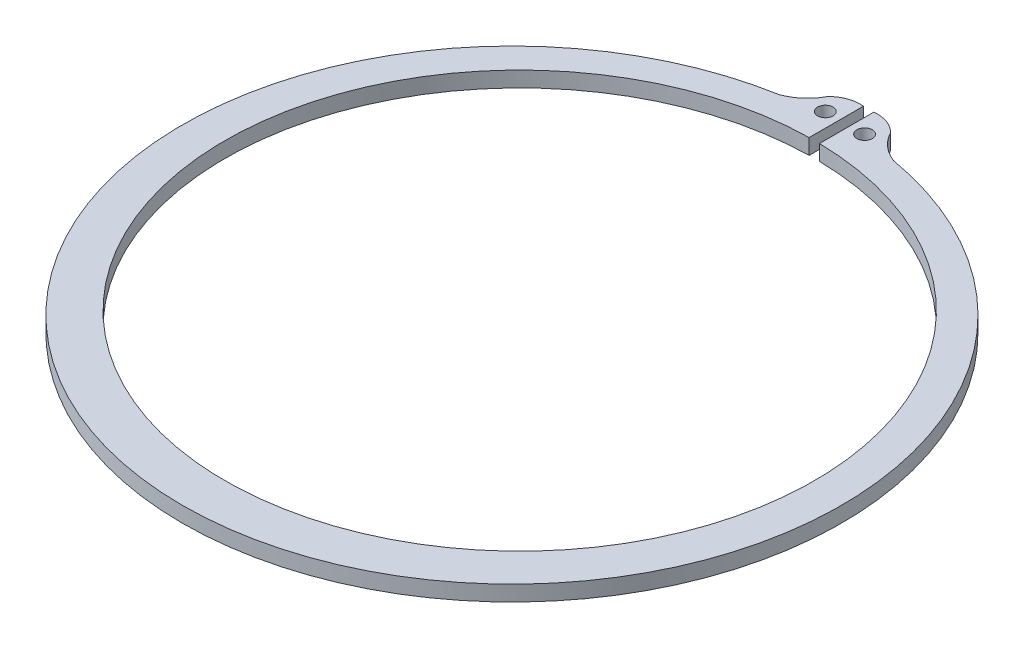
SolidWorks part; units mm, degrees
ref_plane "Plano frontal" through (0, 0, 0) normal (0, 0, 1) x (1, 0, 0)
ref_plane "Plano superior" through (0, 0, 0) normal (0, 1, 0) x (1, 0, 0)
ref_plane "Plano direito" through (0, 0, 0) normal (1, 0, 0) x (0, 0, -1)
sketch "Esboço1" plane through (0, 0, 0) normal (0, 1, 0) x (1, 0, 0)
  line L3 (0, -1) -> (0, 44.4403) construction
  line L4 (-0.6667, 44.9942) -> (-0.6667, 37.9942)
  line L5 (0.6667, 44.9942) -> (0.6667, 37.9942)
  arc A1 (-0.6667, 37.9942) -> (0.6667, 37.9942) centre (0, 0) ccw
  arc A2 (-0.6667, 44.9942) -> (-4.0412, 43.7764) centre (-1.127, 40.9853) ccw
  arc A3 (-4.0412, 43.7764) -> (-7.3611, 40.8577) centre (-9.5407, 46.6843) cw
  arc A4 (4.0412, 43.7764) -> (7.3611, 40.8577) centre (9.5407, 46.6843) ccw
  arc A5 (0.6667, 44.9942) -> (4.0412, 43.7764) centre (1.127, 40.9853) cw
  arc A6 (-7.3611, 40.8577) -> (7.3611, 40.8577) centre (0, -1) ccw
  dimension "D1" = 38
  dimension "D2" = 42.5
extrude "Ressalto-extrusão1" add sketch "Esboço1" along normal blind 2
sketch "Esboço2" plane through (0, 2, 0) normal (0, 1, 0) x (1, 0, 0)
  line L0 (0, 0) -> (0, -5.9097) construction
  circle A0 centre (-2.5323, 41.9441) radius 0.9956
  circle A1 centre (2.5323, 41.9441) radius 0.9956
extrude "Corte-extrusão2" cut sketch "Esboço2" against normal blind 2
